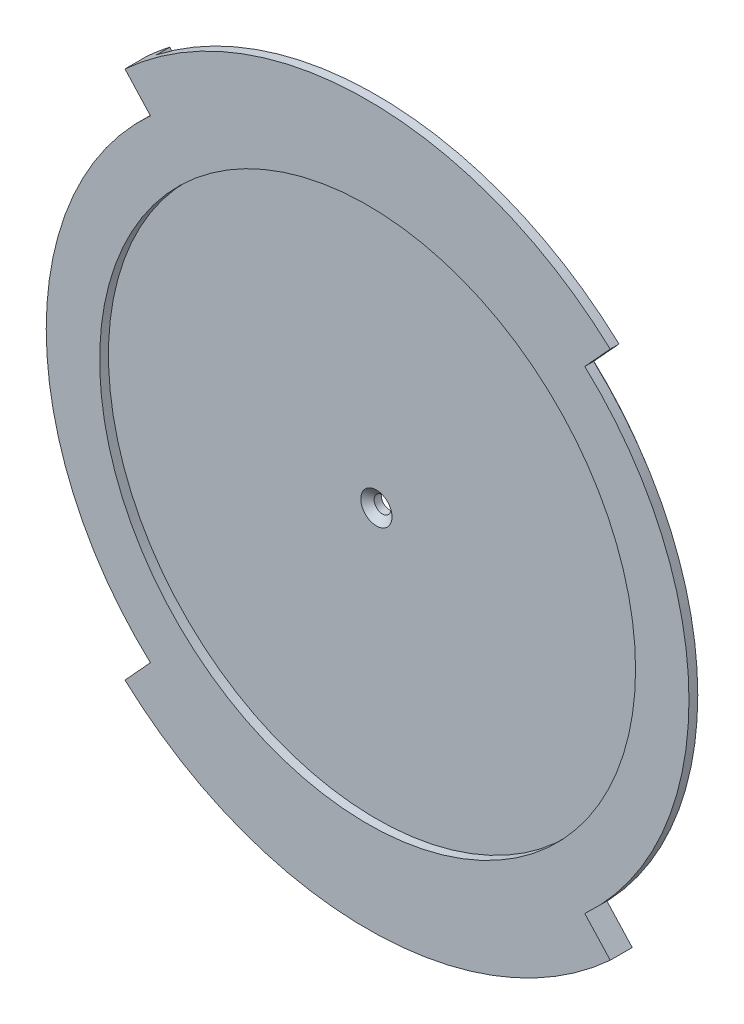
SolidWorks part; units mm, degrees
ref_plane "Front Plane" through (0, 0, 0) normal (0, 0, 1) x (1, 0, 0)
ref_plane "Top Plane" through (0, 0, 0) normal (0, 1, 0) x (1, 0, 0)
ref_plane "Right Plane" through (0, 0, 0) normal (1, 0, 0) x (0, 0, -1)
sketch "Sketch1" plane through (0, 0, 0) normal (0, 1, 0) x (1, 0, 0)
  line L0 (-68.83, 3) -> (-68.83, 0)
  line L2 (0, 0) -> (-60.8489, 0)
  line L3 (0, 0) -> (0, 3)
  line L4 (0, 3) -> (-68.83, 3)
  line L6 (-68.83, 0) -> (-81.53, 0)
  line L8 (-68.83, -2) -> (-81.53, -2)
  line L9 (-81.53, 0) -> (-81.53, -2)
  line L10 (-68.83, -2) -> (-60.8489, -2)
  line L11 (-60.8489, -2) -> (-60.8489, 0)
  dimension "D1" = 3
  dimension "D2" = 81.53
  dimension "D3" = 12.7
  dimension "D4" = 2
revolve "Revolve1" add sketch "Sketch1" angle 360 about L3
sketch "Sketch3" plane through (0, 0, 0) normal (0, 0, 1) x (1, 0, 0)
  line L0 (0, 0) -> (0, 64.9989) construction
  circle A0 centre (0, 0) radius 64.9989
hole_wizard "CSK for #6 Flat Head Machine Screw (100)1" positions "3DSketch2" profile "Sketch4" countersink size "#6" standard "ANSI Inch"
sketch3d "3DSketch2"
  line L0 (0, 0, 0) -> (0, 64.9989, 0) construction
  point P0 (0, 0, 0)
  point P4 (0, 0, 0)
  point P6 (0, 0.3076, 0)
sketch "Sketch4" plane through (0, 0.3076, 0) normal (1, 0, 0) x (0, -1, 0)
  line L0 (0, 0) -> (0, 3)
  line L1 (0, 3) -> (1.8986, 3)
  line L2 (1.8986, 3) -> (1.8986, 1.38)
  line L3 (1.8986, 1.38) -> (3.5433, 0)
  line L5 (3.5433, 0) -> (0, 0)
  line L6 (-1.8987, 1.38) -> (-3.5433, 0) construction
  line L11 (0, -6.35) -> (0, 107.95) construction
  dimension "Thru Hole Dia." = 3.7973
  dimension "Thru Hole Depth" = 3
  dimension "Near C'Sink Dia." = 7.0866
  dimension "Near C'Sink Angle" = 100
sketch "Sketch5" plane through (0, 0, 0) normal (0, 0, -1) x (-1, 0, 0)
  line L0 (-49.3213, 53.7911) -> (-57.9042, 63.1519)
  line L1 (-49.3213, 53.7911) -> (49.3213, 53.7911) construction
  line L3 (-49.3213, 53.7911) -> (-49.3213, -53.7911) construction
  line L4 (-49.3213, -53.7911) -> (49.3213, -53.7911) construction
  line L5 (49.3213, -53.7911) -> (49.3213, 53.7911) construction
  line L6 (-49.3213, -53.7911) -> (-57.9042, -63.1519)
  line L7 (49.3213, 53.7911) -> (55.0996, 60.0931)
  line L8 (49.3213, -53.7911) -> (55.0996, -60.0931)
  arc A1 (-57.9042, 63.1519) -> (-57.9042, -63.1519) centre (0, 0) ccw
  arc A2 (-49.3213, 53.7911) -> (-49.3213, -53.7911) centre (0, 0) ccw
  circle A3 centre (0, 0) radius 81.53 construction
  arc A5 (49.3213, 53.7911) -> (49.3213, -53.7911) centre (0, 0) cw
  arc A6 (55.0996, 60.0931) -> (55.0996, -60.0931) centre (0, 0) cw
  circle M6 centre (0, 0) radius 81.53
  circle M7 centre (0, 0) radius 68.83
extrude "Cut-Extrude1" cut sketch "Sketch5" against normal blind 10 contours L6 L0 M7 M6
sketch "Sketch6" plane through (0, 0, 2) normal (0, 0, 1) x (1, 0, 0)
  line L0 (52.2105, 56.9421) -> (-54.7617, -59.7245) construction
  line L1 (49.3213, 53.7911) -> (55.0996, 60.0931) construction
  line L2 (55.0996, -60.0931) -> (0, 0) construction
  line L3 (0, 0) -> (-54.7617, 59.7245) construction
  line L4 (-54.7617, 59.7245) -> (-49.3213, 53.7911)
  line L5 (-54.7617, -59.7245) -> (-49.3213, -53.7911)
  arc A0 (-54.7617, 59.7245) -> (-54.7617, -59.7245) centre (0, 0) ccw
  arc A1 (-49.3213, 53.7911) -> (-49.3213, -53.7911) centre (0, 0) ccw
  arc A2 (49.3213, -53.7911) -> (49.3213, 53.7911) centre (0, 0) ccw
  arc M6 (55.0996, 60.0931) -> (55.0996, -60.0931) centre (0, 0) ccw
extrude "Cut-Extrude2" cut sketch "Sketch6" against normal through all both and the other way through all contours A1 L4 L5 M6
sketch "Sketch7" plane through (0, 0, 2) normal (0, 0, 1) x (1, 0, 0)
  line L0 (-49.3213, 53.7911) -> (49.3213, -53.7911) construction
  line L1 (44.6842, -57.7009) -> (-44.6842, 57.7009) construction
  line L6 (49.3213, -53.7911) -> (55.0996, -60.0931)
  line L7 (49.3213, -53.7911) -> (55.0996, -60.0931) construction
  line L8 (44.6842, -57.7009) -> (49.9192, -64.4609)
  line L9 (-44.6842, 57.7009) -> (-49.9192, 64.4609)
  line L10 (-49.3213, 53.7911) -> (-55.0996, 60.0931)
  arc A3 (44.6842, -57.7009) -> (49.3213, -53.7911) centre (0, 0) ccw
  arc A4 (-44.6842, 57.7009) -> (-49.3213, 53.7911) centre (0, 0) ccw
  arc A6 (49.9192, -64.4609) -> (55.0996, -60.0931) centre (0, 0) ccw
  arc A7 (-49.9192, 64.4609) -> (-55.0996, 60.0931) centre (0, 0) ccw
extrude "Boss-Extrude1" add sketch "Sketch7" against normal blind 5
sketch "Sketch9" plane through (0, 0, 2) normal (0, 0, 1) x (1, 0, 0)
  line L0 (-54.7617, 59.7245) -> (-55.0996, 60.0931)
  line L1 (-54.7617, -59.7245) -> (-55.0996, -60.0931)
  arc A0 (-55.0996, 60.0931) -> (-55.0996, -60.0931) centre (0, 0) ccw
  arc A1 (-54.7617, 59.7245) -> (-54.7617, -59.7245) centre (0, 0) ccw
extrude "Cut-Extrude3" cut sketch "Sketch9" against normal blind 10
sketch "Sketch8" plane through (0, 0, 2) normal (0, 0, 1) x (1, 0, 0)
  line L0 (3.8695, 75.8859) -> (2.5779, 80.989) construction
  line L1 (0, 0) -> (0, 60.3489) construction
  line L2 (0, 60.3489) -> (0, 81.03) construction
  arc A0 (54.7617, 59.7245) -> (-54.7617, 59.7245) centre (0, 0) ccw construction
  circle A1 centre (0, 0) radius 60.3489 construction
  circle A2 centre (0, 0) radius 60.3489 construction
